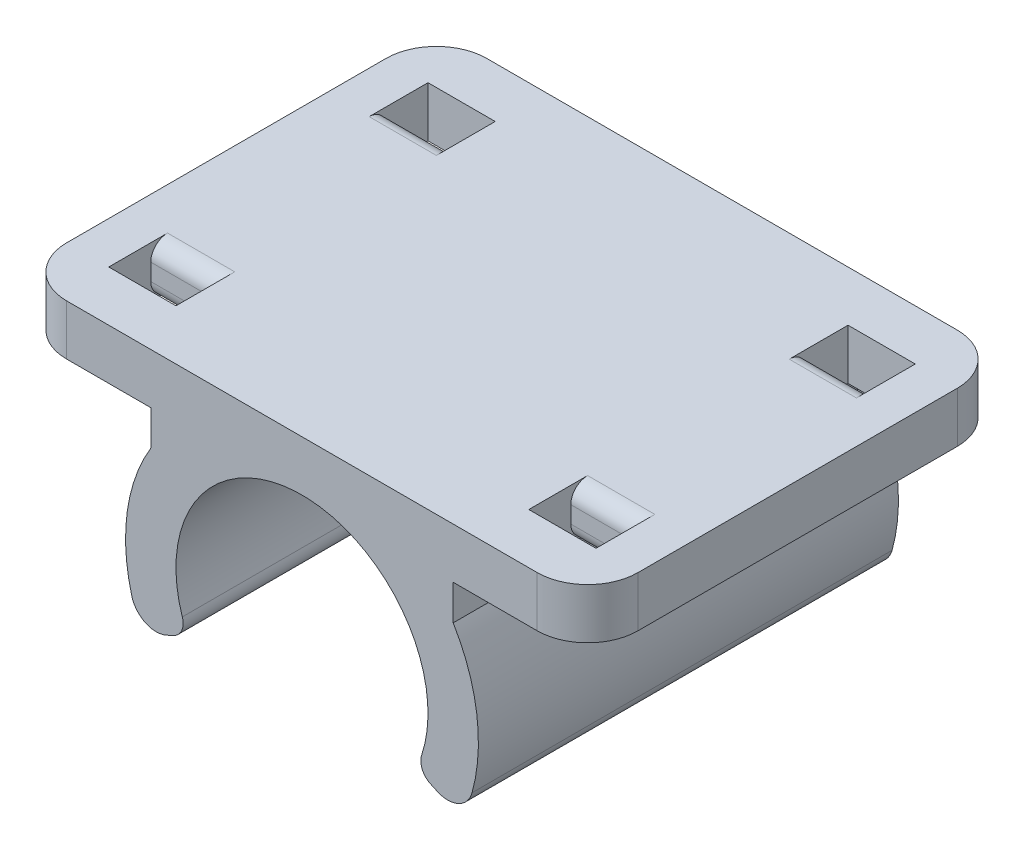
SolidWorks part; units mm, degrees
ref_plane "Plano frontal" through (0, 0, 0) normal (0, 0, 1) x (1, 0, 0)
ref_plane "Plano superior" through (0, 0, 0) normal (0, 1, 0) x (1, 0, 0)
ref_plane "Plano direito" through (0, 0, 0) normal (1, 0, 0) x (0, 0, -1)
sketch "Esboço1" plane through (0, 0, 0) normal (0, 0, 1) x (1, 0, 0)
  line L0 (-17, 10.5) -> (17, 10.5)
  line L1 (-7.6501, -3.5673) -> (-9.5162, -4.4375)
  line L2 (0, 0) -> (-10.5, 0) construction
  line L3 (0, 0) -> (0, 10.5) construction
  line L4 (7.6501, -3.5673) -> (9.5162, -4.4375)
  line L5 (-17, 10.5) -> (-17, 7.5)
  line L6 (-17, 7.5) -> (-9, 7.5)
  line L7 (-9, 7.5) -> (-9, 5.4083)
  line L8 (9, 7.5) -> (9, 5.4083)
  line L9 (17, 7.5) -> (9, 7.5)
  line L10 (17, 10.5) -> (17, 7.5)
  arc A0 (7.123, -2.3479) -> (-7.123, -2.3479) centre (0, 0) ccw
  arc A1 (9.5162, -4.4375) -> (9, 5.4083) centre (0, 0) ccw
  arc A2 (7.6501, -3.5673) -> (7.123, -2.3479) centre (8.0727, -2.661) cw
  arc A3 (-7.6501, -3.5673) -> (-7.123, -2.3479) centre (-8.0727, -2.661) ccw
  arc A4 (-9, 5.4083) -> (-9.5162, -4.4375) centre (0, 0) ccw
  point P6 (0, 10.5)
  point P13 (6.7973, -3.1696)
  point P16 (-6.7973, -3.1696)
  dimension "D1" = 15
  dimension "D3" = 21
  dimension "D5" = 1
  dimension "D2" = 10.5
  dimension "D4" = 25
  dimension "D6" = 3
  dimension "D7" = 9
  dimension "D8" = 8
extrude "Ressalto-extrusão1" add sketch "Esboço1" along normal blind 25
fillet "Filete1" radius 1.5 2 edges at (9.5162, -4.4375, 12.5) (-9.5162, -4.4375, 12.5)
sketch "Esboço3" plane through (0, 10.5, 0) normal (0, 1, 0) x (1, 0, 0)
  line L0 (-12.5, -12.5) -> (12.5, -12.5) construction
  line L1 (17, -25) -> (17, 0) construction
  line L2 (-12.5, -4.25) -> (-12.5, -20.75) construction
  line L3 (0, 0) -> (0, -25) construction
  line L4 (17, -25) -> (-17, -25) construction
  line L5 (17, 0) -> (-17, 0) construction
  line L6 (-14.5, -3) -> (-10.5, -3)
  line L7 (-14.5, -3) -> (-14.5, -5.5)
  line L8 (-14.5, -5.5) -> (-10.5, -5.5)
  line L9 (-10.5, -3) -> (-10.5, -5.5)
  line L10 (-14.5, -3) -> (-10.5, -5.5) construction
  line L11 (-14.5, -5.5) -> (-10.5, -3) construction
  line L13 (-14.5, -19.5) -> (-10.5, -22) construction
  line L14 (-14.5, -22) -> (-10.5, -19.5) construction
  line L15 (-10.5, -22) -> (-10.5, -19.5)
  line L16 (-14.5, -19.5) -> (-10.5, -19.5)
  line L17 (-14.5, -22) -> (-14.5, -19.5)
  line L18 (-14.5, -22) -> (-10.5, -22)
  line L19 (12.5, -4.25) -> (12.5, -20.75) construction
  line L20 (14.5, -22) -> (10.5, -19.5) construction
  line L21 (14.5, -19.5) -> (10.5, -22) construction
  line L22 (14.5, -5.5) -> (10.5, -3) construction
  line L23 (14.5, -3) -> (10.5, -5.5) construction
  line L24 (14.5, -22) -> (10.5, -22)
  line L25 (14.5, -22) -> (14.5, -19.5)
  line L26 (14.5, -19.5) -> (10.5, -19.5)
  line L27 (10.5, -22) -> (10.5, -19.5)
  line L28 (10.5, -3) -> (10.5, -5.5)
  line L29 (14.5, -5.5) -> (10.5, -5.5)
  line L30 (14.5, -3) -> (14.5, -5.5)
  line L31 (14.5, -3) -> (10.5, -3)
  point P3 (0, -12.5)
  point P6 (17, -12.5)
  point P10 (-12.5, -12.5)
  point P15 (0, -12.5)
  dimension "D1" = 25
  dimension "D2" = 4
  dimension "D3" = 2.5
  dimension "D4" = 3
extrude "Corte-extrusão1" cut sketch "Esboço3" against normal up to next
fillet "Filete2" radius 1 8 edges at (-12.5, 7.5, 5.5) (12.5, 7.5, 5.5) (12.5, 7.5, 19.5) (12.5, 10.5, 19.5) (12.5, 10.5, 5.5) (-12.5, 7.5, 19.5) (-12.5, 10.5, 19.5) (-12.5, 10.5, 5.5)
fillet "Filete3" radius 3 4 edges at (-17, 9, 0) (17, 9, 0) (17, 9, 25) (-17, 9, 25)
